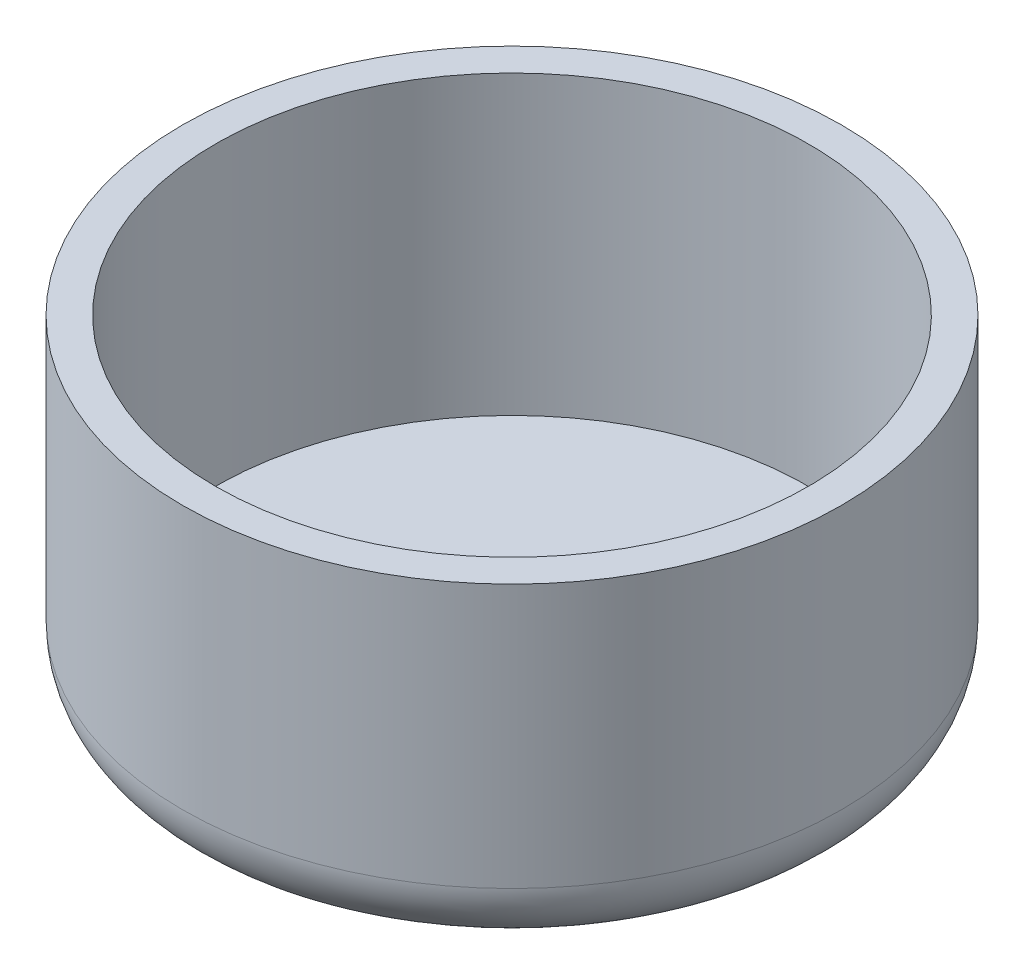
SolidWorks part; units mm, degrees
ref_plane "Front Plane" through (0, 0, 0) normal (0, 0, 1) x (1, 0, 0)
ref_plane "Top Plane" through (0, 0, 0) normal (0, 1, 0) x (1, 0, 0)
ref_plane "Right Plane" through (0, 0, 0) normal (1, 0, 0) x (0, 0, -1)
sketch "Sketch2" plane through (0, 0, 0) normal (0, 1, 0) x (1, 0, 0)
  circle A0 centre (0, 0) radius 100
  point P3 (0, 0)
  point P4 (0, 0)
extrude "Boss-Extrude1" add sketch "Sketch2" along normal blind 100
sketch "Sketch3" plane through (0, 100, 0) normal (0, 1, 0) x (1, 0, 0)
  circle A0 centre (0, 0) radius 90
extrude "Cut-Extrude1" cut sketch "Sketch3" against normal blind 90
fillet "Fillet1" radius 20 1 edges at (0, 0, 100)
sketch "Sketch4" plane through (0, 0, 0) normal (0, -1, 0) x (1, 0, 0)
  circle A0 centre (0, 0) radius 4
extrude "Boss-Extrude2" add sketch "Sketch4" along normal blind 3
